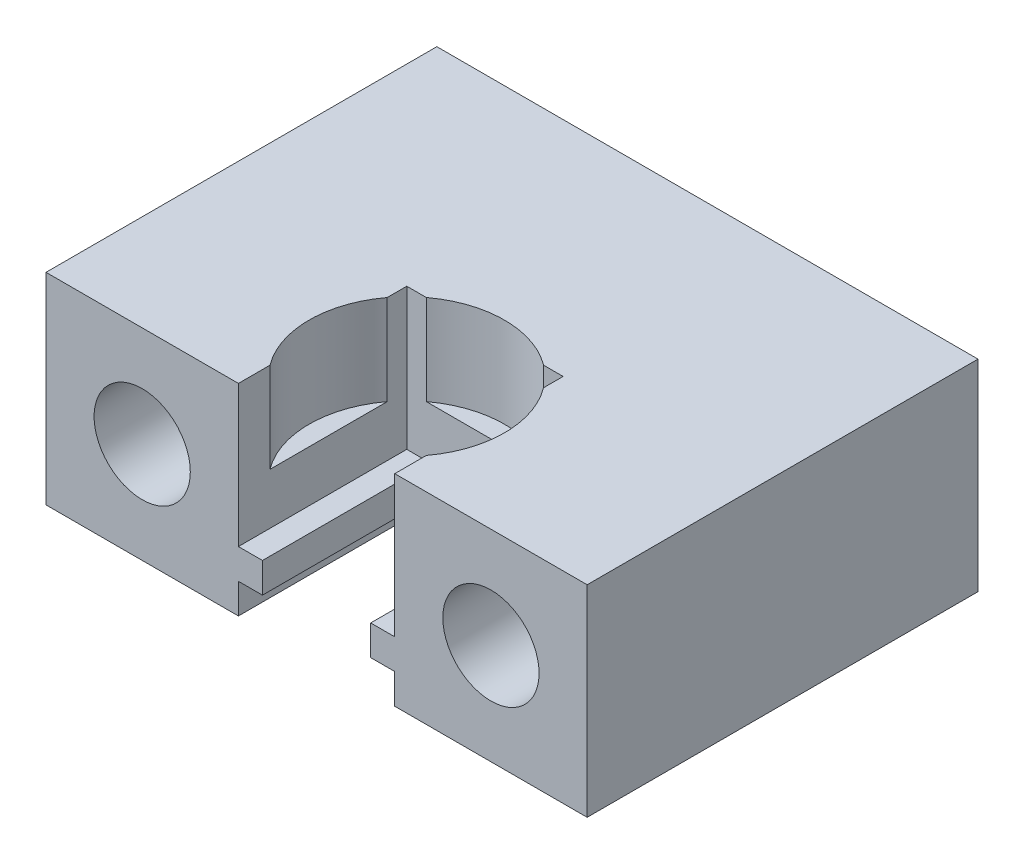
SolidWorks part; units mm, degrees
ref_plane "Front Plane" through (0, 0, 0) normal (0, 0, 1) x (1, 0, 0)
ref_plane "Top Plane" through (0, 0, 0) normal (0, 1, 0) x (1, 0, 0)
ref_plane "Right Plane" through (0, 0, 0) normal (1, 0, 0) x (0, 0, -1)
sketch "Sketch1" plane through (0, 0, 0) normal (0, 0, 1) x (1, 0, 0)
  line L0 (-9, 0) -> (9, 0) construction
  line L1 (-9, 6.7) -> (9, 6.7)
  line L2 (-9, 6.7) -> (-9, 0)
  line L3 (-9, 0) -> (9, 0)
  line L4 (9, 6.7) -> (9, 0)
  line L5 (-9, 6.7) -> (9, 0) construction
  line L6 (-9, 0) -> (9, 6.7) construction
  line L7 (9, 9.4077) -> (9, 6.7) construction
  line L8 (-10.1621, 6.7) -> (10.1621, 6.7) construction
  line L9 (-9, 6.7) -> (-9, 9.4077) construction
  point P4 (0, 3.35)
  point P5 (9, 6.7)
extrude "Boss-Extrude1" add sketch "Sketch1" along normal blind 13
sketch "Sketch2" plane through (0, 0, 0) normal (0, -1, 0) x (1, 0, 0)
  line L0 (-2.6, 12.6) -> (-2.6, 13)
  line L1 (-2.6, 7.4) -> (2.6, 7.4)
  line L2 (-2.6, 7.4) -> (-2.6, 12.6)
  line L3 (-2.6, 12.6) -> (2.6, 12.6) construction
  line L4 (2.6, 7.4) -> (2.6, 12.6)
  line L5 (-2.6, 7.4) -> (2.6, 12.6) construction
  line L6 (-2.6, 12.6) -> (2.6, 7.4) construction
  line L7 (-9, 13) -> (9, 13) construction
  line L8 (-2.6, 13) -> (2.6, 13)
  line L9 (2.6, 13) -> (2.6, 12.6)
  circle A0 centre (0, 10) radius 3 construction
  dimension "D1" = 6
  dimension "D2" = 5.2
  dimension "D3" = 5.2
extrude "Cut-Extrude1" cut sketch "Sketch2" against normal up to next
sketch "Sketch3" plane through (0, 6.7, 0) normal (0, 1, 0) x (1, 0, 0)
  circle A0 centre (0, -10) radius 3.25
  circle A1 centre (0, -10) radius 3 construction
  dimension "D1" = 0.25
extrude "Cut-Extrude2" cut sketch "Sketch3" against normal blind 3
sketch "Sketch4" plane through (0, 0, 13) normal (0, 0, 1) x (1, 0, 0)
  line L0 (-2.6, 6.7) -> (-2.6, 0) construction
  line L1 (-2.6, 1) -> (-1.8, 1)
  line L2 (-2.6, 1) -> (-2.6, 2)
  line L3 (-2.6, 2) -> (-1.8, 2)
  line L4 (-1.8, 1) -> (-1.8, 2)
  line L5 (-2.6, 1) -> (-1.8, 2) construction
  line L6 (-2.6, 2) -> (-1.8, 1) construction
  line L7 (2.6, 6.7) -> (2.6, 0) construction
  line L8 (2.6, 1) -> (1.8, 1)
  line L9 (2.6, 1) -> (2.6, 2)
  line L10 (2.6, 2) -> (1.8, 2)
  line L11 (1.8, 1) -> (1.8, 2)
  line L12 (2.6, 1) -> (1.8, 2) construction
  line L13 (2.6, 2) -> (1.8, 1) construction
  line L14 (-2.6, 0) -> (2.6, 0) construction
  point P4 (-2.2, 1.5)
  point P11 (2.2, 1.5)
  dimension "D1" = 1
  dimension "D2" = 0.8
  dimension "D3" = 1
extrude "Boss-Extrude2" add sketch "Sketch4" against normal up to surface (5.6 mm away) up to face at (0, 4.275, 7.4)
sketch "Sketch8" plane through (0, 0, 13) normal (0, 0, 1) x (1, 0, 0)
  line L1 (-9, 0) -> (-2.6, 0) construction
  line L2 (-9, 0) -> (-9, 6.7) construction
  line L3 (-9, 6.7) -> (-2.6, 6.7) construction
  line L4 (-2.6, 0) -> (-2.6, 6.7) construction
  line L5 (-9, 0) -> (-2.6, 6.7) construction
  line L6 (-9, 6.7) -> (-2.6, 0) construction
  circle A0 centre (-5.8, 3.35) radius 1.6
  point P4 (-5.8, 3.35)
  dimension "D1" = 3.2
extrude "Cut-Extrude3" cut sketch "Sketch8" against normal up to next
mirror "Mirror1" about plane through (0, 0, 0) normal (1, 0, 0) of "Cut-Extrude3"
